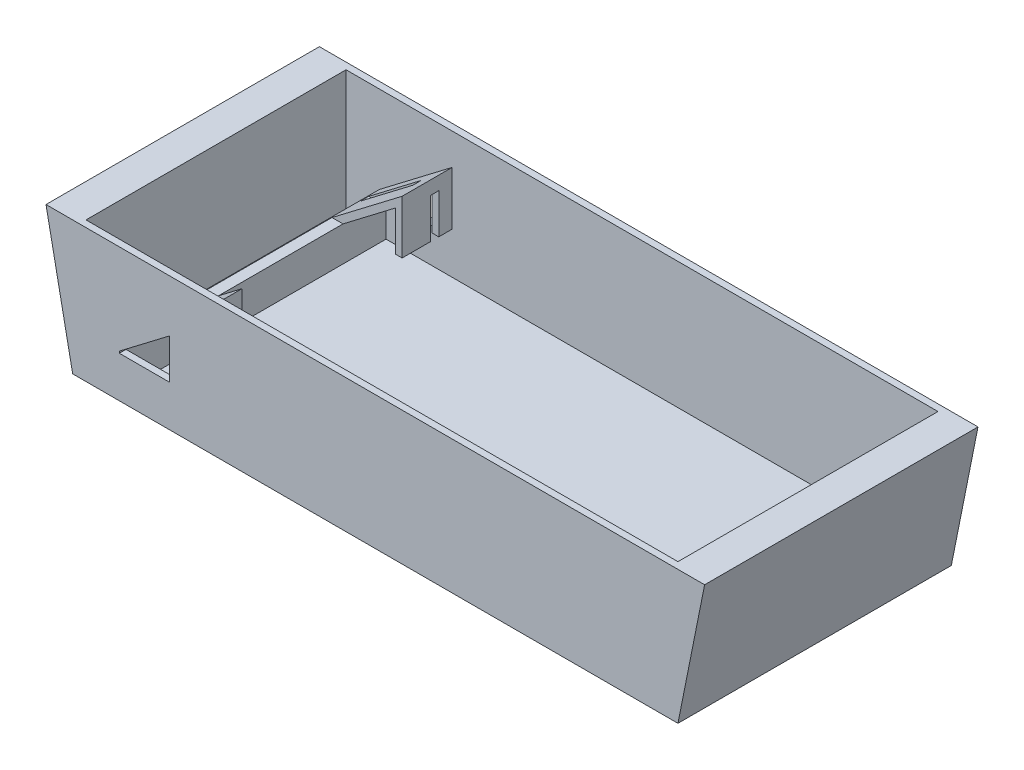
SolidWorks part; units mm, degrees
ref_plane "Plan de face" through (0, 0, 0) normal (0, 0, 1) x (1, 0, 0)
ref_plane "Plan de dessus" through (0, 0, 0) normal (0, 1, 0) x (1, 0, 0)
ref_plane "Plan de droite" through (0, 0, 0) normal (1, 0, 0) x (0, 0, -1)
sketch "Esquisse1" plane through (0, 0, 0) normal (0, 0, 1) x (1, 0, 0)
  line L0 (0, 0) -> (-197.55, 0)
  line L1 (-197.55, 0) -> (-197.55, 40)
  line L2 (-197.55, 40) -> (0, 40)
  line L3 (0, 40) -> (0, 0)
  dimension "D1" = 40
  dimension "D2" = 197.55
extrude "Boss.-Extru.1" add sketch "Esquisse1" along normal blind 82
sketch "Esquisse2" plane through (0, 40, 0) normal (0, 1, 0) x (1, 0, 0)
  line L0 (-187.55, -2) -> (-187.55, -80)
  line L1 (-187.55, -80) -> (-10, -80)
  line L2 (-10, -80) -> (-10, -2)
  line L3 (-10, -2) -> (-187.55, -2)
  line L5 (0, -82) -> (-197.55, -82) construction
  line L7 (0, -82) -> (0, 0) construction
  line L8 (-197.55, -82) -> (-197.55, 0) construction
  dimension "D1" = 78
  dimension "D2" = 2
  dimension "D3" = 10
  dimension "D4" = 10
extrude "Enlèv. mat.-Extru.1" cut sketch "Esquisse2" against normal blind 38
sketch "Esquisse3" plane through (0, 0, 0) normal (0, 0, 1) x (1, 0, 0)
  line L0 (-197.55, 40) -> (-189.55, 0)
  line L2 (-197.55, 0) -> (0, 0) construction
  line L3 (0, 40) -> (-8, 0)
  line L4 (-8, 0) -> (0, 0)
  line L5 (0, 0) -> (0, 40)
  line L6 (-197.55, 40) -> (-197.55, 0)
  line L7 (-197.55, 0) -> (-189.55, 0)
  dimension "D1" = 8
  dimension "D2" = 8
extrude "Enlèv. mat.-Extru.4" cut sketch "Esquisse3" along normal blind 82
sketch "Esquisse6" plane through (0, 0, 2) normal (0, 0, 1) x (1, 0, 0)
  line L1 (-175.55, 12.9146) -> (-175.55, 0.9146)
  line L2 (-157.74, 14.5) -> (-157.74, 26.5)
  line L8 (-175.55, 12.9146) -> (-157.74, 26.5)
  line L9 (-175.55, 0.9146) -> (-177.55, 0.9146)
  line L10 (-177.55, 0.9146) -> (-177.55, 13.9044)
  line L14 (-177.55, 13.9044) -> (-155.74, 30.541)
  line L15 (-157.74, 14.5) -> (-155.74, 14.5)
  line L16 (-155.74, 14.5) -> (-155.74, 30.541)
  line L17 (-187.55, 2) -> (-187.55, 40) construction
  line L18 (-10, 2) -> (-187.55, 2) construction
  point P12 (-156.74, 14.5)
  dimension "D1" = 22.4
  dimension "D2" = 2
  dimension "D3" = 2
  dimension "D4" = 2
  dimension "D5" = 12
  dimension "D6" = 12
  dimension "D7" = 10
  dimension "D8" = 12.5
extrude "Boss.-Extru.6" add sketch "Esquisse6" along normal blind 78.5
sketch "Esquisse8" plane through (-155.74, 0, 0) normal (1, 0, 0) x (0, 0, -1)
  line L0 (-65, 30.541) -> (-65, 14.5)
  line L1 (-80, 30.541) -> (-2, 30.541) construction
  line L2 (-80, 14.5) -> (-2, 14.5) construction
  line L3 (-65, 14.5) -> (-17, 14.5)
  line L4 (-17, 14.5) -> (-17, 30.541)
  line L5 (-17, 30.541) -> (-65, 30.541)
  line L6 (-80, 30.541) -> (-80, 14.5) construction
  line L7 (-2, 14.5) -> (-2, 30.541) construction
  dimension "D1" = 15
  dimension "D2" = 15
extrude "Enlèv. mat.-Extru.5" cut sketch "Esquisse8" against normal blind 26.4
sketch "Esquisse9" plane through (-155.74, 0, 0) normal (1, 0, 0) x (0, 0, -1)
  line L0 (-76, 14.5) -> (-76, 26.7)
  line L1 (-80, 14.5) -> (-65, 14.5) construction
  line L2 (-76, 26.7) -> (-73.5, 26.7)
  line L3 (-73.5, 26.7) -> (-73.5, 14.5)
  line L4 (-80, 30.541) -> (-80, 14.5) construction
  line L5 (-76, 14.5) -> (-73.5, 14.5)
  dimension "D1" = 12.2
  dimension "D2" = 2.5
  dimension "D3" = 4
extrude "Enlèv. mat.-Extru.6" cut sketch "Esquisse9" against normal blind 26.4
sketch "Esquisse10" plane through (-155.74, 0, 0) normal (1, 0, 0) x (0, 0, -1)
  line L0 (-8.5, 14.5) -> (-8.5, 26.5)
  line L1 (-17, 14.5) -> (-2, 14.5) construction
  line L2 (-8.5, 26.5) -> (-6, 26.5)
  line L3 (-6, 26.5) -> (-6, 14.5)
  line L4 (-6, 14.5) -> (-8.5, 14.5)
  line L5 (-2, 14.5) -> (-2, 30.541) construction
  dimension "D1" = 2.5
  dimension "D2" = 4
  dimension "D3" = 12
extrude "Enlèv. mat.-Extru.7" cut sketch "Esquisse10" against normal blind 26.4
sketch "Esquisse11" plane through (0, 0, 0) normal (0, 0, -1) x (-1, 0, 0)
  line L0 (175.55, 12.9146) -> (160.55, 24.3565)
  line L1 (175.55, 12.9146) -> (157.74, 26.5) construction
  line L2 (160.55, 24.3565) -> (160.55, 12.3565)
  line L3 (160.55, 12.3565) -> (175.55, 12.3565)
  line L4 (175.55, 12.9146) -> (175.55, 0.9146) construction
  line L5 (175.55, 12.3565) -> (175.55, 12.9146)
  dimension "D1" = 12
  dimension "D2" = 15
extrude "Enlèv. mat.-Extru.9" cut sketch "Esquisse11" against normal blind 82
